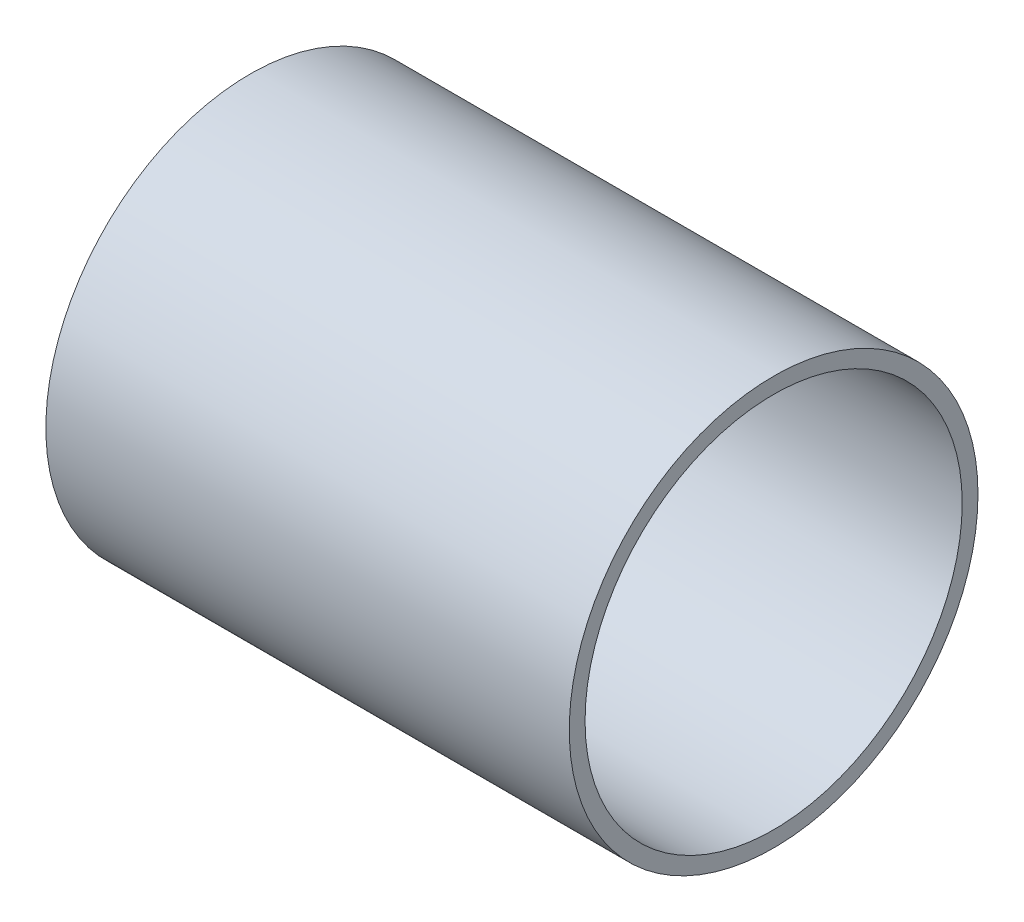
SolidWorks part; units mm, degrees
ref_plane "Front Plane" through (0, 0, 0) normal (0, 0, 1) x (1, 0, 0)
ref_plane "Top Plane" through (0, 0, 0) normal (0, 1, 0) x (1, 0, 0)
ref_plane "Right Plane" through (0, 0, 0) normal (1, 0, 0) x (0, 0, -1)
sketch "Sketch3" plane through (0, 0, 0) normal (1, 0, 0) x (0, 0, -1)
  circle A0 centre (0, 0) radius 43.2406
extrude "Boss-Extrude2" add sketch "Sketch3" along normal blind 110.744
sketch "Sketch4" plane through (110.744, 0, 0) normal (1, 0, 0) x (0, 0, -1)
  circle A0 centre (0, 0) radius 39.8978
extrude "Cut-Extrude1" cut sketch "Sketch4" against normal blind 110.744
